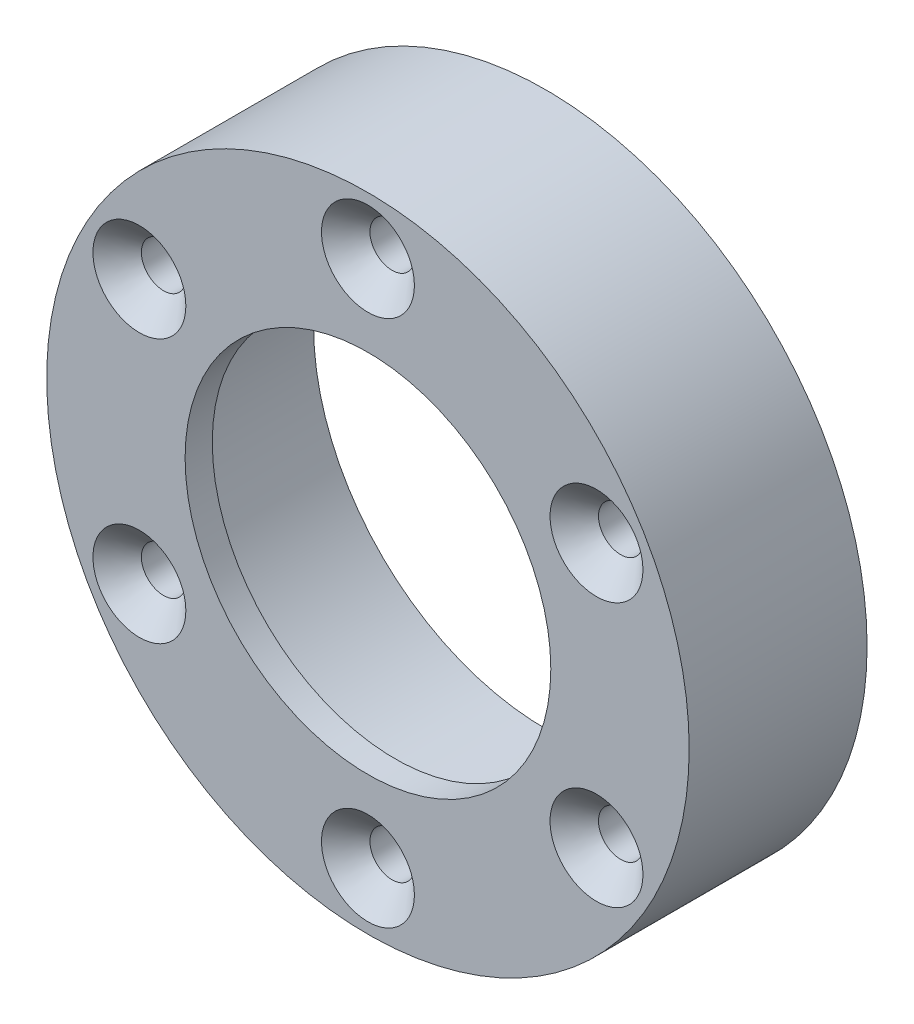
SolidWorks part; units mm, degrees
material "AISI 316 Annealed Stainless Steel Bar (SS)"
ref_plane "Front Plane" through (0, 0, 0) normal (0, 0, 1) x (1, 0, 0)
ref_plane "Top Plane" through (0, 0, 0) normal (0, 1, 0) x (1, 0, 0)
ref_plane "Right Plane" through (0, 0, 0) normal (1, 0, 0) x (0, 0, -1)
sketch "Sketch1" plane through (0, 0, 0) normal (0, 0, 1) x (1, 0, 0)
  circle A0 centre (0, 0) radius 32.5
  dimension "D1" = 65
extrude "Boss-Extrude1" add sketch "Sketch1" along normal blind 18
hole_wizard "CSK for M4 Flat Head Machine Screw1" positions "Sketch2" profile "Sketch3" countersink size "M4" standard "ANSI Metric" end condition through all
sketch "Sketch2" plane through (0, 0, 18) normal (0, 0, 1) x (1, 0, 0)
  point P0 (0, 26.7)
  dimension "D1" = 26.7
sketch "Sketch3" plane through (0, 26.7, 18) normal (1, 0, 0) x (0, -1, 0)
  line L0 (0, 0) -> (0, 18)
  line L1 (0, 18) -> (2.25, 18)
  line L2 (2.25, 18) -> (2.25, 2.45)
  line L3 (2.25, 2.45) -> (4.7, 0)
  line L5 (4.7, 0) -> (0, 0)
  line L6 (-2.25, 2.45) -> (-4.7, 0) construction
  line L11 (0, -6.35) -> (0, 107.95) construction
  dimension "Thru Hole Dia." = 4.5
  dimension "Thru Hole Depth" = 18
  dimension "Near C'Sink Dia." = 9.4
  dimension "Near C'Sink Angle" = 90
pattern_circular "CirPattern1" count 6 over 360 about axis through (0, 0, 0) along (0, 0, 1) of "CSK for M4 Flat Head Machine Screw1"
sketch "Sketch4" plane through (0, 0, 0) normal (0, 0, -1) x (-1, 0, 0)
  circle A0 centre (0, 0) radius 18.5
  dimension "D1" = 37
extrude "Cut-Extrude1" cut sketch "Sketch4" against normal blind 30
sketch "Sketch5" plane through (0, 0, 0) normal (0, 0, -1) x (-1, 0, 0)
  circle A0 centre (0, 0) radius 23.5
  dimension "D1" = 47
extrude "Cut-Extrude2" cut sketch "Sketch5" against normal blind 15.25
